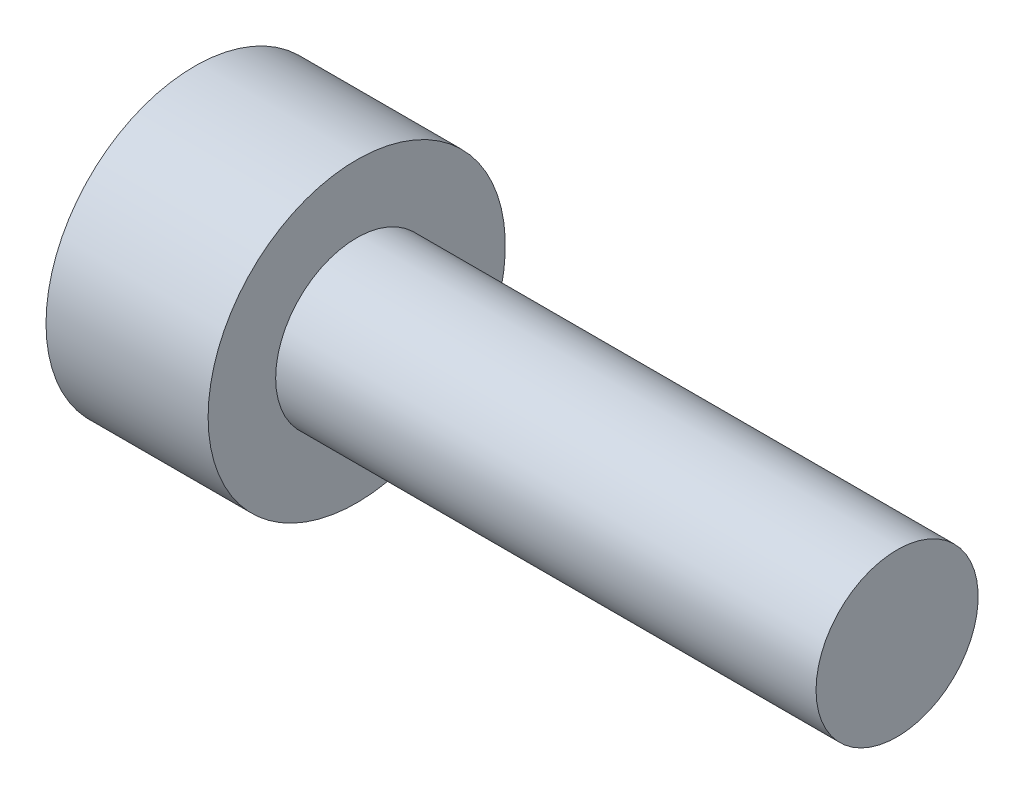
SolidWorks part; units mm, degrees
material "AISI Type 316L stainless steel"
ref_plane "Front Plane" through (0, 0, 0) normal (0, 0, 1) x (1, 0, 0)
ref_plane "Top Plane" through (0, 0, 0) normal (0, 1, 0) x (1, 0, 0)
ref_plane "Right Plane" through (0, 0, 0) normal (1, 0, 0) x (0, 0, -1)
sketch "Axial profile (mm)" plane through (0, 0, 0) normal (0, 0, 1) x (1, 0, 0)
  line L0 (-110, 0) -> (75, 0) construction
  line L1 (128.7, 0) -> (141.7, 0)
  line L2 (141.7, 0) -> (141.7, 1.5)
  line L3 (141.7, 1.5) -> (131.7, 1.5)
  line L4 (131.7, 1.5) -> (131.7, 2.75)
  line L5 (131.7, 2.75) -> (128.7, 2.75)
  line L6 (128.7, 2.75) -> (128.7, 0)
revolve "Full revolution" add sketch "Axial profile (mm)" angle 360 about L0
